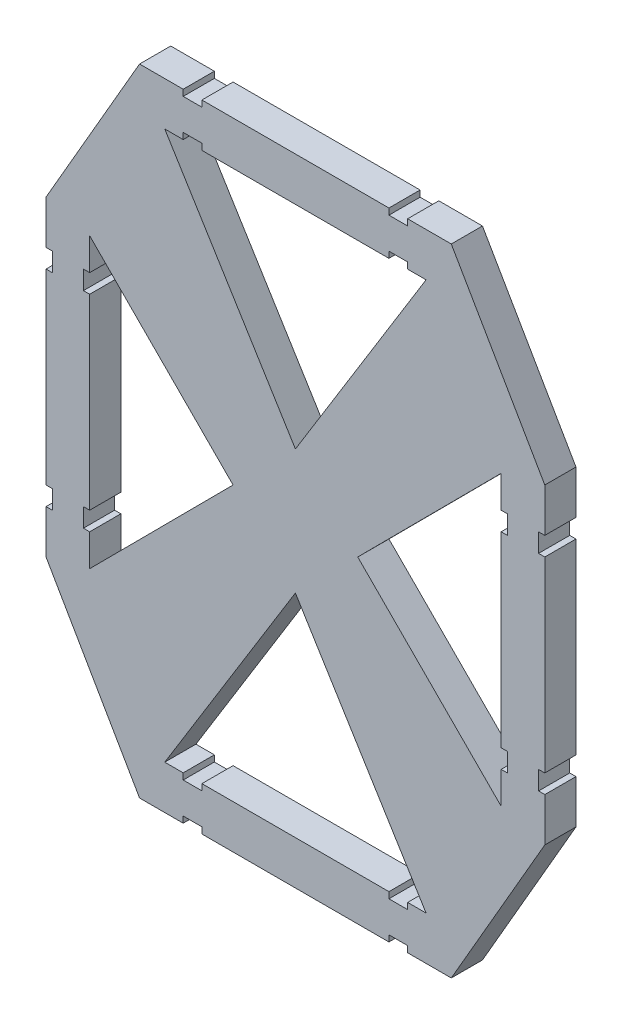
SolidWorks part; units mm, degrees
ref_plane "Plan de face" through (0, 0, 0) normal (0, 0, 1) x (1, 0, 0)
ref_plane "Plan de dessus" through (0, 0, 0) normal (0, 1, 0) x (1, 0, 0)
ref_plane "Plan de droite" through (0, 0, 0) normal (1, 0, 0) x (0, 0, -1)
sketch "Esquisse1" plane through (0, 0, 0) normal (0, 0, 1) x (1, 0, 0)
  line L0 (-275.9159, -82.8503) -> (-268.9159, -82.8503)
  line L1 (-268.9159, -82.8503) -> (-268.9159, -81.8503)
  line L2 (-268.9159, -81.8503) -> (-265.9159, -81.8503)
  line L3 (-265.9159, -81.8503) -> (-265.9159, -82.8503)
  line L4 (-265.9159, -82.8503) -> (-235.9159, -82.8503)
  line L5 (-235.9159, -82.8503) -> (-235.9159, -81.8503)
  line L6 (-235.9159, -81.8503) -> (-232.9159, -81.8503)
  line L7 (-232.9159, -81.8503) -> (-232.9159, -82.8503)
  line L8 (-232.9159, -82.8503) -> (-225.9159, -82.8503)
  line L9 (-225.9159, -82.8503) -> (-210.9159, -56.8696)
  line L10 (-225.9159, 19.1112) -> (-232.9159, 19.1112)
  line L11 (-232.9159, 19.1112) -> (-232.9159, 18.1112)
  line L12 (-232.9159, 18.1112) -> (-235.9159, 18.1112)
  line L13 (-235.9159, 18.1112) -> (-235.9159, 19.1112)
  line L14 (-235.9159, 19.1112) -> (-265.9159, 19.1112)
  line L15 (-265.9159, 19.1112) -> (-265.9159, 18.1112)
  line L16 (-265.9159, 18.1112) -> (-268.9159, 18.1112)
  line L17 (-268.9159, 18.1112) -> (-268.9159, 19.1112)
  line L18 (-268.9159, 19.1112) -> (-275.9159, 19.1112)
  line L19 (-275.9159, 19.1112) -> (-290.9159, -6.8696)
  line L20 (-283.9159, -49.8696) -> (-283.9159, -54.9939)
  line L21 (-283.9159, -8.7452) -> (-283.9159, -13.8696)
  line L22 (-284.9159, -49.8696) -> (-283.9159, -49.8696)
  line L23 (-284.9159, -46.8696) -> (-284.9159, -49.8696)
  line L24 (-283.9159, -46.8696) -> (-284.9159, -46.8696)
  line L25 (-283.9159, -16.8696) -> (-283.9159, -46.8696)
  line L26 (-284.9159, -16.8696) -> (-283.9159, -16.8696)
  line L27 (-284.9159, -13.8696) -> (-284.9159, -16.8696)
  line L28 (-283.9159, -13.8696) -> (-284.9159, -13.8696)
  line L30 (-210.9159, -56.8696) -> (-210.9159, -49.8696)
  line L31 (-210.9159, -49.8696) -> (-211.9159, -49.8696)
  line L32 (-211.9159, -49.8696) -> (-211.9159, -46.8696)
  line L33 (-211.9159, -46.8696) -> (-210.9159, -46.8696)
  line L34 (-210.9159, -46.8696) -> (-210.9159, -16.8696)
  line L35 (-210.9159, -16.8696) -> (-211.9159, -16.8696)
  line L36 (-211.9159, -16.8696) -> (-211.9159, -13.8696)
  line L37 (-211.9159, -13.8696) -> (-210.9159, -13.8696)
  line L38 (-210.9159, -13.8696) -> (-210.9159, -6.8696)
  line L39 (-210.9159, -6.8696) -> (-225.9159, 19.1112)
  line L40 (-268.9159, 12.1112) -> (-271.8745, 12.1112)
  line L41 (-229.9574, 12.1112) -> (-232.9159, 12.1112)
  line L42 (-268.9159, 13.1112) -> (-268.9159, 12.1112)
  line L43 (-265.9159, 13.1112) -> (-268.9159, 13.1112)
  line L44 (-265.9159, 12.1112) -> (-265.9159, 13.1112)
  line L45 (-235.9159, 12.1112) -> (-265.9159, 12.1112)
  line L46 (-235.9159, 13.1112) -> (-235.9159, 12.1112)
  line L47 (-232.9159, 13.1112) -> (-235.9159, 13.1112)
  line L48 (-232.9159, 12.1112) -> (-232.9159, 13.1112)
  line L50 (-290.9159, -6.8696) -> (-290.9159, -13.8696)
  line L51 (-290.9159, -13.8696) -> (-289.9159, -13.8696)
  line L52 (-289.9159, -13.8696) -> (-289.9159, -16.8696)
  line L53 (-289.9159, -16.8696) -> (-290.9159, -16.8696)
  line L54 (-290.9159, -16.8696) -> (-290.9159, -46.8696)
  line L55 (-290.9159, -46.8696) -> (-289.9159, -46.8696)
  line L56 (-289.9159, -46.8696) -> (-289.9159, -49.8696)
  line L57 (-289.9159, -49.8696) -> (-290.9159, -49.8696)
  line L58 (-290.9159, -49.8696) -> (-290.9159, -56.8696)
  line L59 (-290.9159, -56.8696) -> (-275.9159, -82.8503)
  line L60 (-283.9159, -54.9939) -> (-260.9159, -31.8698)
  line L61 (-271.8745, -75.8503) -> (-250.9159, -41.8698)
  line L62 (-217.9159, -54.9939) -> (-240.9159, -31.8698)
  line L63 (-250.9159, -41.8698) -> (-229.9574, -75.8503)
  line L64 (-229.9574, 12.1112) -> (-250.9159, -21.8698)
  line L65 (-217.9159, -8.7452) -> (-240.9159, -31.8698)
  line L66 (-271.8745, 12.1112) -> (-250.9159, -21.8698)
  line L67 (-260.9159, -31.8698) -> (-283.9159, -8.7452)
  line L70 (-217.9159, -13.8696) -> (-217.9159, -8.7452)
  line L71 (-217.9159, -54.9939) -> (-217.9159, -49.8696)
  line L72 (-216.9159, -13.8696) -> (-217.9159, -13.8696)
  line L73 (-216.9159, -16.8696) -> (-216.9159, -13.8696)
  line L74 (-217.9159, -16.8696) -> (-216.9159, -16.8696)
  line L75 (-217.9159, -46.8696) -> (-217.9159, -16.8696)
  line L76 (-216.9159, -46.8696) -> (-217.9159, -46.8696)
  line L77 (-216.9159, -49.8696) -> (-216.9159, -46.8696)
  line L78 (-217.9159, -49.8696) -> (-216.9159, -49.8696)
  line L80 (-232.9159, -75.8503) -> (-229.9574, -75.8503)
  line L81 (-271.8745, -75.8503) -> (-268.9159, -75.8503)
  line L82 (-232.9159, -76.8503) -> (-232.9159, -75.8503)
  line L83 (-235.9159, -76.8503) -> (-232.9159, -76.8503)
  line L84 (-235.9159, -75.8503) -> (-235.9159, -76.8503)
  line L85 (-265.9159, -75.8503) -> (-235.9159, -75.8503)
  line L86 (-265.9159, -76.8503) -> (-265.9159, -75.8503)
  line L87 (-268.9159, -76.8503) -> (-265.9159, -76.8503)
  line L88 (-268.9159, -75.8503) -> (-268.9159, -76.8503)
  dimension "D1" = 50
  dimension "D2" = 30
  dimension "D3" = 7
  dimension "D4" = 3
  dimension "D5" = 5
  dimension "D6" = 7
  dimension "D9" = 7
  dimension "D11" = 7
  dimension "D12" = 7
  dimension "D13" = 66
sketch "Esquisse2" plane through (0, 0, 0) normal (0, 0, 1) x (1, 0, 0)
  line L1 (-225.9657, -54.0611) -> (-275.9657, -54.0611)
  line L2 (-225.9657, -54.0611) -> (-225.9657, -4.0611)
  line L3 (-225.9657, -4.0611) -> (-275.9657, -4.0611)
  line L4 (-275.9657, -54.0611) -> (-275.9657, -4.0611)
  circle A0 centre (-228.4657, -6.5611) radius 1.5
  circle A1 centre (-273.4657, -6.5611) radius 1.5
  circle A2 centre (-228.4657, -51.5611) radius 1.5
  circle A3 centre (-273.4657, -51.5611) radius 1.5
  dimension "D3" = 2.5
  dimension "D5" = 2
  dimension "D1" = 50
  dimension "D2" = 50
  dimension "D4" = 2.5
  dimension "D6" = 2
extrude "Boss.-Extru.4" add sketch "Esquisse1" along normal blind 5
